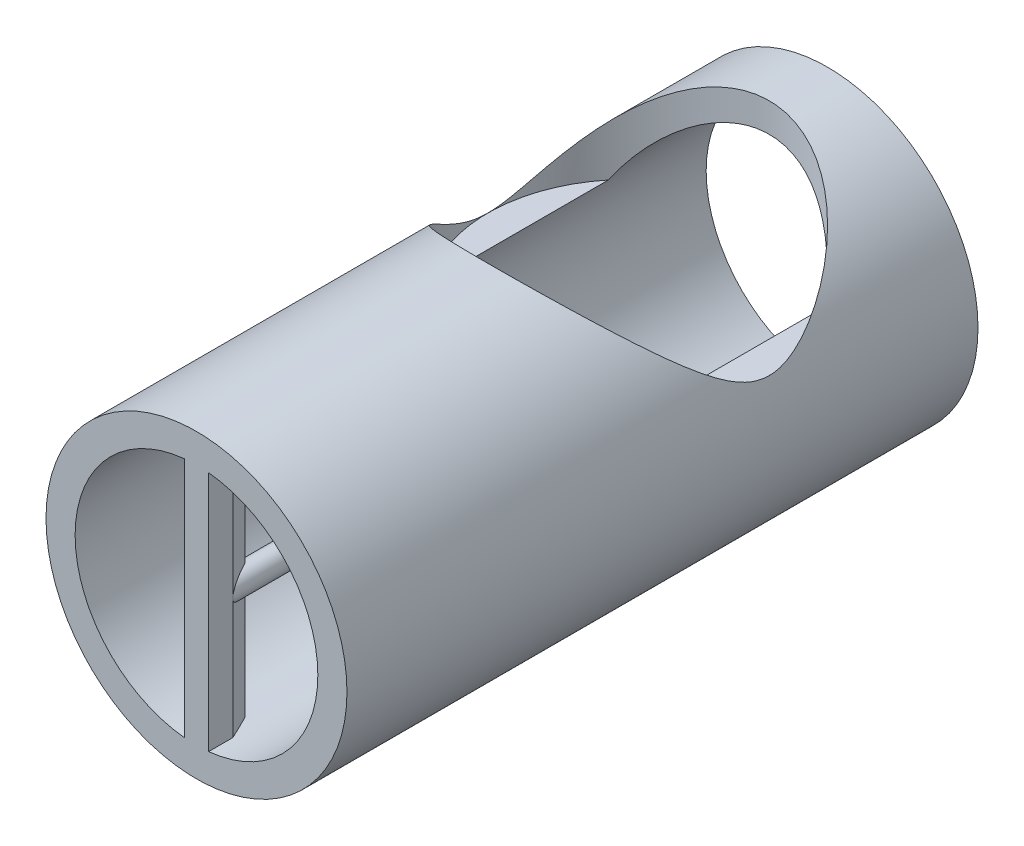
SolidWorks part; units mm, degrees
ref_plane "Alzado" through (0, 0, 0) normal (0, 0, 1) x (1, 0, 0)
ref_plane "Planta" through (0, 0, 0) normal (0, 1, 0) x (1, 0, 0)
ref_plane "Vista lateral" through (0, 0, 0) normal (1, 0, 0) x (0, 0, -1)
sketch "Croquis1" plane through (0, 0, 0) normal (0, 0, 1) x (1, 0, 0)
  circle A0 centre (0, 0) radius 31
  circle A1 centre (0, 0) radius 25
extrude "Saliente-Extruir1" add sketch "Croquis1" along normal blind 130
ref_plane "Plano1" through (0, 40, 0) normal (0, 1, 0) x (1, 0, 0)
sketch "Croquis3" plane through (0, 40, 0) normal (0, 1, 0) x (1, 0, 0)
  circle A0 centre (0, -41) radius 29
extrude "Cortar-Extruir1" cut sketch "Croquis3" against normal blind 29.05
sketch "Croquis5" plane through (0, 0, 0) normal (0, 1, 0) x (1, 0, 0)
  line L0 (-2.5, -130) -> (2.5, -130)
  line L1 (0, -120) -> (-2.5, -125)
  line L2 (2.5, -130) -> (2.5, -125)
  line L3 (-2.5, -130) -> (-2.5, -125)
  line L5 (0, -120) -> (2.5, -125)
extrude "Saliente-Extruir2" add sketch "Croquis5" along normal up to next and the other way up to next
sketch "Croquis6" plane through (0, 0, 130) normal (0, 0, 1) x (1, 0, 0)
  circle A0 centre (0, 0) radius 2.5
extrude "Saliente-Extruir3" add sketch "Croquis6" against normal blind 20
